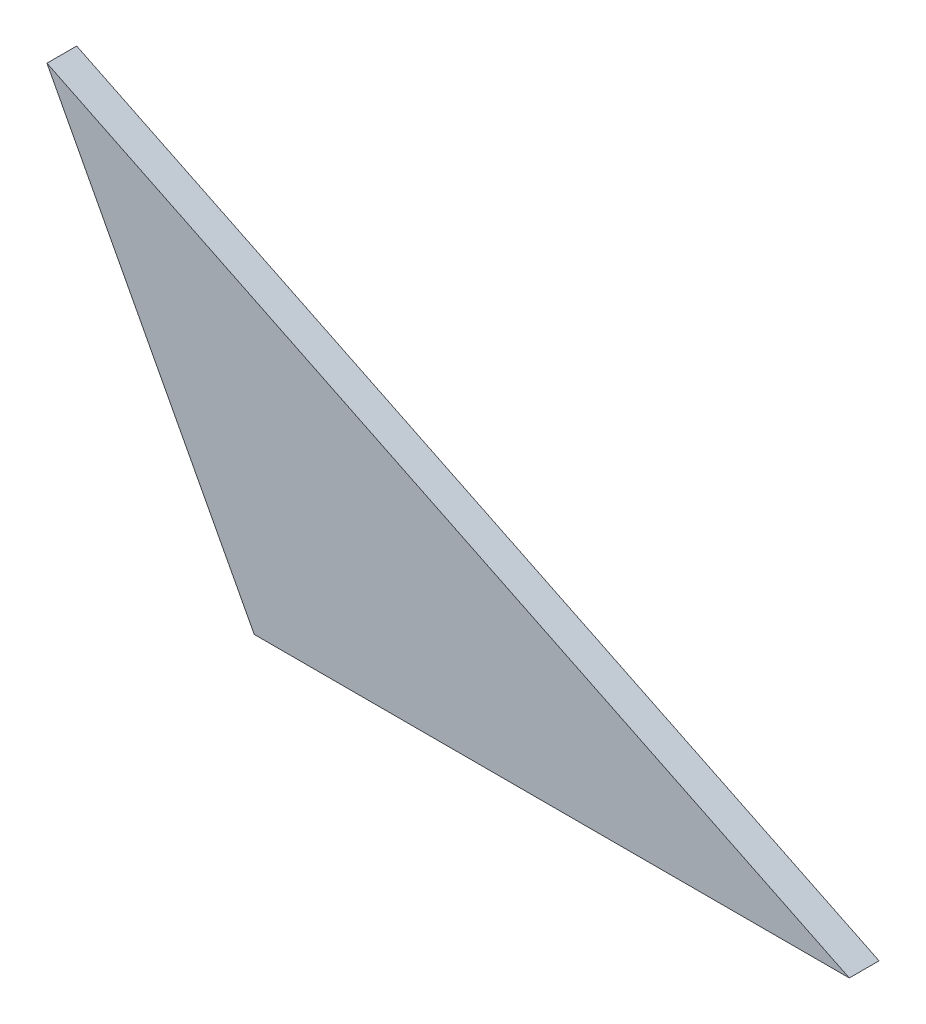
SolidWorks part; units mm, degrees
ref_plane "Front Plane" through (0, 0, 0) normal (0, 0, 1) x (1, 0, 0)
ref_plane "Top Plane" through (0, 0, 0) normal (0, 1, 0) x (1, 0, 0)
ref_plane "Right Plane" through (0, 0, 0) normal (1, 0, 0) x (0, 0, -1)
sketch "Sketch1" plane through (0, 0, 0) normal (1, 0, 0) x (0, 0, -1)
  line L0 (-0.025, 0.1646) -> (0.025, 0.1646)
  arc A0 (0.025, 0.1646) -> (-0.025, 0.1646) centre (0, 0.1646) ccw
  dimension "D1" = 0.05
sketch "Sketch2" plane through (0, 0, 0) normal (0, 0, 1) x (1, 0, 0)
  line L0 (0, 0.1771) -> (0.1393, -0.0858)
  line L1 (0, 0.1646) -> (0, 0.1896) construction
  line L2 (0.1393, -0.0858) -> (0.5393, -0.0858)
  line L3 (0, 0.1771) -> (0.5393, -0.0858)
  dimension "D1" = 0.2975
  dimension "D2" = 0.4
  dimension "D3" = 0.6
extrude "Boss-Extrude1" add sketch "Sketch2" along normal mid plane 0.02
